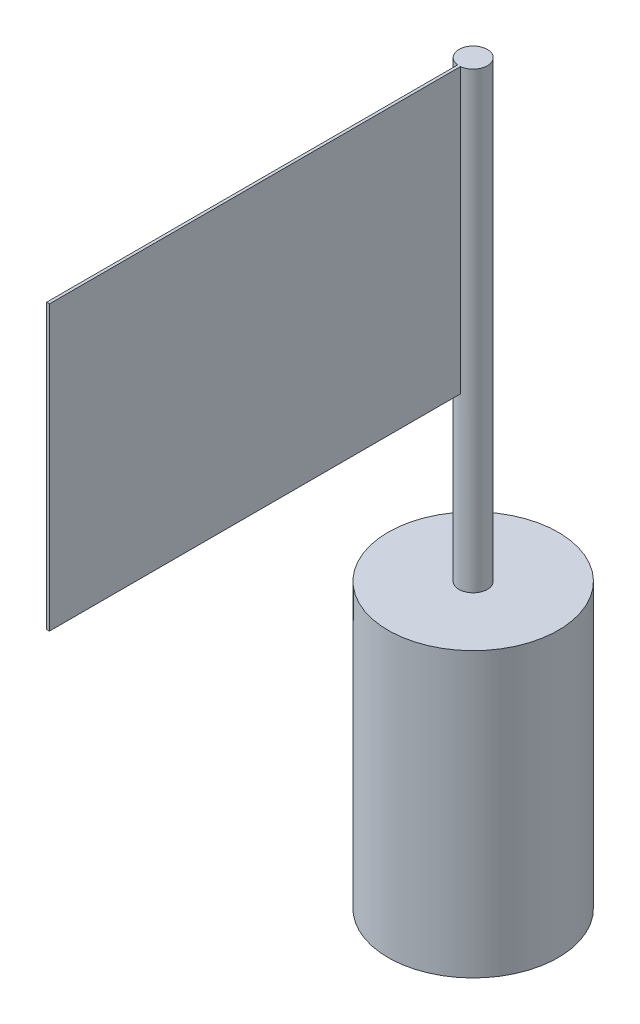
SolidWorks part; units mm, degrees
ref_plane "Front Plane" through (0, 0, 0) normal (0, 0, 1) x (1, 0, 0)
ref_plane "Top Plane" through (0, 0, 0) normal (0, 1, 0) x (1, 0, 0)
ref_plane "Right Plane" through (0, 0, 0) normal (1, 0, 0) x (0, 0, -1)
sketch "Sketch1" plane through (0, 0, 0) normal (0, 0, 1) x (1, 0, 0)
  line L0 (0, 0) -> (-30, 0)
  line L1 (-30, 0) -> (-30, 100)
  line L2 (-30, 100) -> (-5, 100)
  line L3 (-5, 100) -> (-5, 260)
  line L4 (-5, 260) -> (0, 260)
  line L5 (0, 260) -> (0, 0)
  dimension "D1" = 30
  dimension "D2" = 100
  dimension "D3" = 160
  dimension "D4" = 5
revolve "Revolve1" add sketch "Sketch1" angle 360 about L5
sketch "Sketch2" plane through (0, 0, 0) normal (0, 0, 1) x (1, 0, 0)
  line L0 (5, 260) -> (-5, 260) construction
  line L1 (-0.5, 160) -> (0.5, 160)
  line L2 (-0.5, 160) -> (-0.5, 260)
  line L3 (-0.5, 260) -> (0.5, 260)
  line L4 (0.5, 160) -> (0.5, 260)
  line L5 (-0.5, 160) -> (0.5, 260) construction
  line L6 (-0.5, 260) -> (0.5, 160) construction
  line L7 (0, 260) -> (0, 210) construction
  point P0 (0, 210)
  dimension "D1" = 1
  dimension "D2" = 100
extrude "Boss-Extrude1" add sketch "Sketch2" along normal blind 150
